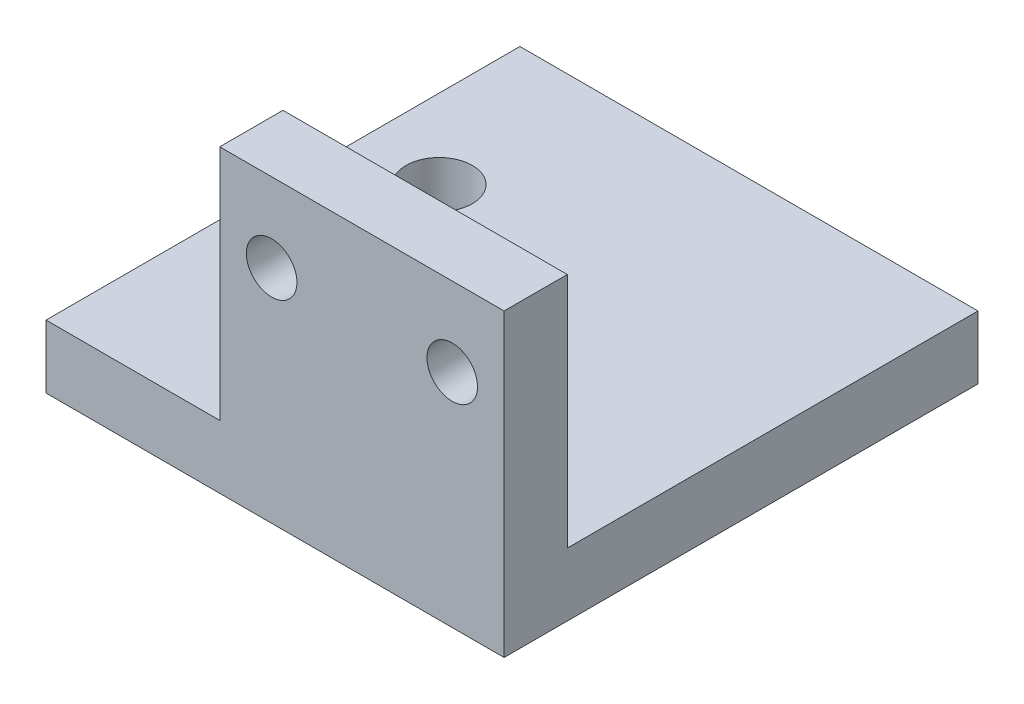
SolidWorks part; units mm, degrees
material "1060 Alloy"
ref_plane "Front Plane" through (0, 0, 0) normal (0, 0, 1) x (1, 0, 0)
ref_plane "Top Plane" through (0, 0, 0) normal (0, 1, 0) x (1, 0, 0)
ref_plane "Right Plane" through (0, 0, 0) normal (1, 0, 0) x (0, 0, -1)
sketch "Sketch1" plane through (0, 0, 0) normal (0, 0, 1) x (1, 0, 0)
  line L1 (-9, -9.5) -> (9, -9.5)
  line L2 (-9, -9.5) -> (-9, 9.5)
  line L3 (-9, 9.5) -> (9, 9.5)
  line L4 (9, -9.5) -> (9, 9.5)
  line L5 (-9, -9.5) -> (9, 9.5) construction
  line L6 (-9, 9.5) -> (9, -9.5) construction
  point P0 (0, 0)
  dimension "D1" = 19
  dimension "D2" = 18
extrude "Boss-Extrude1" add sketch "Sketch1" along normal mid plane 4
sketch "Sketch2" plane through (0, 0, 2) normal (0, 0, -1) x (-1, 0, 0)
  line L0 (9, 9.5) -> (9, -9.5) construction
  line L1 (20, -9.5) -> (-9, -9.5)
  line L2 (20, -9.5) -> (20, -5.5)
  line L3 (20, -5.5) -> (-9, -5.5)
  line L4 (-9, -9.5) -> (-9, -5.5)
  line L5 (20, -9.5) -> (-9, -5.5) construction
  line L6 (20, -5.5) -> (-9, -9.5) construction
  point P4 (5.5, -7.5)
  dimension "D1" = 4
  dimension "D2" = 11
extrude "Boss-Extrude2" add sketch "Sketch2" along normal blind 30
hole_wizard "M3 Clearance Hole1" positions "Sketch3" profile "Sketch4" hole size "M3" standard "ISO" end condition through all
sketch "Sketch3" plane through (0, 0, 2) normal (0, 0, 1) x (1, 0, 0)
  point P0 (-5.715, 4.5028)
  point P3 (5.715, 4.5028)
sketch "Sketch4" plane through (-5.715, 4.5028, 2) normal (1, 0, 0) x (0, -1, 0)
  line L0 (0, 0) -> (0, 30)
  line L1 (0, 30) -> (1.6, 30)
  line L2 (1.6, 30) -> (1.6, 0)
  line L5 (1.6, 0) -> (0, 0)
  line L11 (0, -6.35) -> (0, 107.95) construction
  dimension "Thru Hole Dia." = 3.2
  dimension "Thru Hole Depth" = 30
hole_wizard "Tapped Hole for M4x0.7 Helicoil1" positions "Sketch5" profile "Sketch6" tap size "M4x0.7" standard "Helicoil® Metric" end condition through all
sketch "Sketch5" plane through (0, -9.5, 0) normal (0, -1, 0) x (-1, 0, 0)
  point P4 (14.9858, 17.875)
sketch "Sketch6" plane through (-14.9858, -9.5, -17.875) normal (1, 0, 0) x (0, 0, -1)
  line L0 (0, 0) -> (0, 19)
  line L1 (0, 19) -> (2.1, 19)
  line L2 (2.1, 19) -> (2.1, 0)
  line L5 (2.1, 0) -> (0, 0)
  line L11 (0, -6.35) -> (0, 107.95) construction
  dimension "Thru Tap Drill Dia." = 4.2
  dimension "Thru Tap Drill Depth" = 19
cosmetic thread "Hole Thread1" parameters "D1"=4, "D2"=5.007
